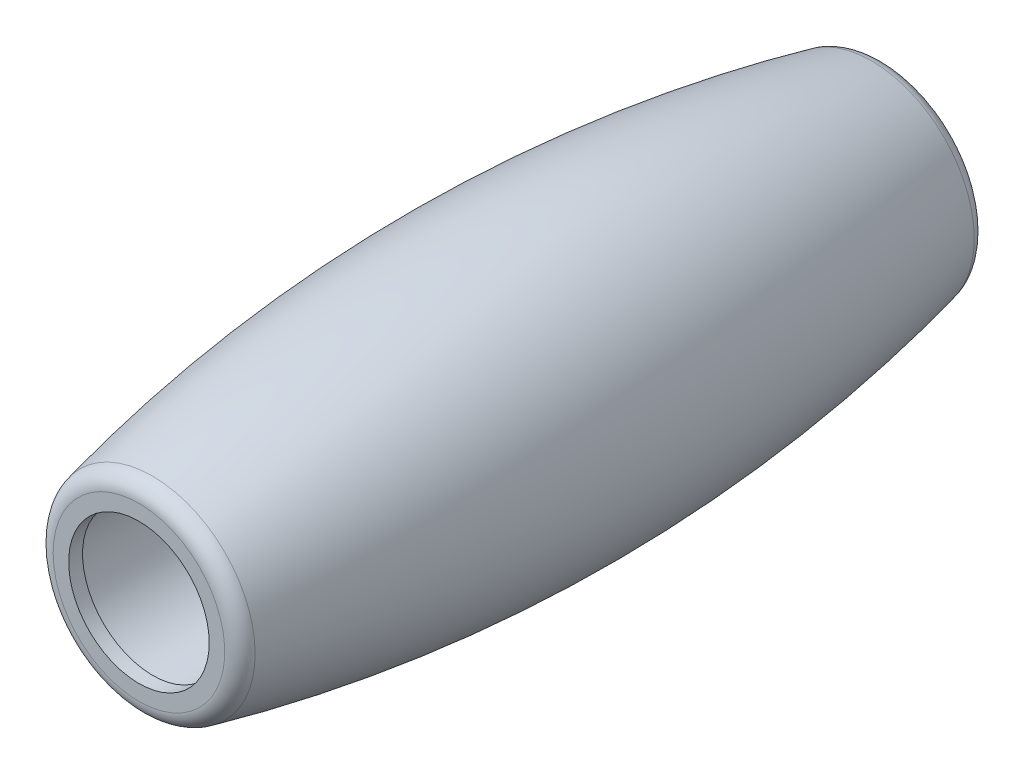
SolidWorks part; units mm, degrees
material "BUTYL"
ref_plane "Front Plane" through (0, 0, 0) normal (0, 0, 1) x (1, 0, 0)
ref_plane "Top Plane" through (0, 0, 0) normal (0, 1, 0) x (1, 0, 0)
ref_plane "Right Plane" through (0, 0, 0) normal (1, 0, 0) x (0, 0, -1)
sketch "Sketch1" plane through (0, 0, 0) normal (1, 0, 0) x (0, 0, -1)
  line L0 (-21.5, 0) -> (21.5, 0) construction
  line L1 (21.5, 0) -> (21.5, 5.7385) construction
  line L2 (-21.5, 0) -> (-21.5, 5.7385) construction
  line L3 (21.5, 5.7385) -> (21.5, 4.05)
  line L4 (20.7, 4.5) -> (-20.7, 4.5)
  line L5 (-21.5, 4.05) -> (-21.5, 5.7385)
  line L6 (20.7, 4.5) -> (20.7, 4.05)
  line L7 (20.7, 4.05) -> (21.5, 4.05)
  line L8 (-20.7, 4.5) -> (-20.7, 4.05)
  line L9 (-20.7, 4.05) -> (-21.5, 4.05)
  arc A0 (21.5, 5.7385) -> (-21.5, 5.7385) centre (0, -85.0327) ccw
  dimension "D1" = 85.0327
  dimension "D2" = 93.2827
  dimension "D3" = 21.5
  dimension "D4" = 4.5
  dimension "D5" = 4.05
  dimension "D6" = 0.8
revolve "Revolve1" add sketch "Sketch1" angle 360 about L0
fillet "Fillet1" radius 1 2 edges at (5.7385, 0, -21.5) (5.7385, 0, 21.5)
